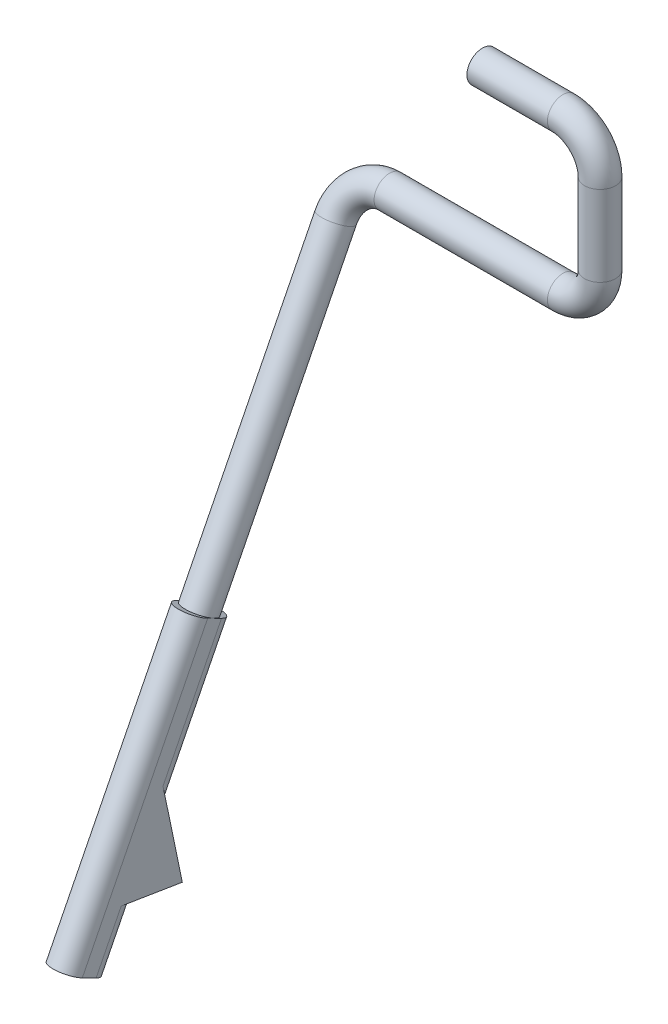
SolidWorks part; units mm, degrees
material "Alloy Steel"
ref_plane "Front Plane" through (0, 0, 0) normal (0, 0, 1) x (1, 0, 0)
ref_plane "Top Plane" through (0, 0, 0) normal (0, 1, 0) x (1, 0, 0)
ref_plane "Right Plane" through (0, 0, 0) normal (1, 0, 0) x (0, 0, -1)
sketch "Sketch2" plane through (0, 0, 0) normal (0, 0, 1) x (1, 0, 0)
  line L0 (0, 0) -> (-13, 0)
  line L1 (6, -6) -> (6, -25)
  arc A0 (0, 0) -> (6, -6) centre (0, -6) cw
  point P6 (6, 0)
  dimension "D3" = 6
  dimension "D1" = 19
  dimension "D2" = 25
sketch3d "3DSketch2"
  line L0 (0, -25, 0) -> (-28, -25, 0)
  line L1 (6, -25, 0) -> (-34, -25, 0) construction
  line L3 (-34, -30.3582, 2.7) -> (-34, -114.3029, 45)
  line L4 (-34, -25, 0) -> (-34, -25, 45) construction
  line L5 (0, 0, 0) -> (-13, 0, 0) construction
  line L6 (6, -6, 0) -> (6, -25, 0) construction
  line L7 (0, 0, 0) -> (-13, 0, 0)
  line L8 (6, -6, 0) -> (6, -19, 0)
  arc A0 (0, 0, 0) -> (6, -6, 0) centre (0, -6, 0) ccw construction
  arc A1 (0, 0, 0) -> (6, -6, 0) centre (0, -6, 0) ccw
  arc A2 (-28, -25, 0) -> (-34, -30.3582, 2.7) centre (-28, -30.3582, 2.7) ccw
  arc A3 (0, -25, 0) -> (6, -19, 0) centre (0, -19, 0) ccw
  point P10 (0, -6, -6)
  point P12 (0, -6, -6)
  point P15 (-34, -25, 0)
  point P17 (-28, -27.6582, 8.0582)
  point P20 (6, -25, 0)
  point P22 (0, -19, 6)
  dimension "D5" = 6
  dimension "D1" = 40
  dimension "D3" = 100
  dimension "D4" = 45
ref_plane "Plane1" through (-13, 0, 0) normal (1, 0, 0) x (0, 0, -1)
sketch "Sketch3" plane through (-13, 0, 0) normal (1, 0, 0) x (0, 0, -1)
  circle A0 centre (0, 0) radius 2.5
  dimension "D1" = 5
sweep "Sweep1" add profiles "Sketch3" path "3DSketch2"
sketch "Sketch4" plane through (0, -109.2404, 55.0466) normal (0, -0.893, 0.45) x (1, 0, 0)
  line L0 (-34, -10) -> (-34, -12.5) construction
  line L1 (-31.5, -10) -> (-31.5, -12.5)
  line L2 (-36.5, -10) -> (-36.5, -12.5)
  arc A0 (-31.5, -10) -> (-36.5, -10) centre (-34, -10) ccw
  arc A1 (-36.5, -12.5) -> (-31.5, -12.5) centre (-34, -12.5) ccw
  circle A3 centre (-34, -11.25) radius 2.5
  circle A4 centre (-34, -11.25) radius 2.5
  point P3 (-34, -11.25)
  circle M7 centre (-34, -11.25) radius 2.5
  dimension "D2" = 2.5
  dimension "D3" = 2.5
  dimension "D1" = 0
extrude "Boss-Extrude1" add sketch "Sketch4" against normal blind 45 contours L1 A0 L2 A4 M7 | L2 A1 L1 A4 M7 | L0 A4 M7 | L0 A4 M7
sketch "Sketch5" plane through (-31.5, 0, 0) normal (1, 0, 0) x (0, 0, -1)
  line L5 (-39.8337, -106.8281) -> (-29.9633, -108.4327)
  line L6 (-23.6337, -74.6791) -> (-43.8837, -114.8654) construction
  line L7 (-29.9633, -108.4327) -> (-33.0837, -93.4327)
  line L8 (-33.0837, -93.4327) -> (-39.8337, -106.8281)
  line L9 (-46.1163, -113.7404) -> (-43.8837, -114.8654) construction
  dimension "D1" = 9
  dimension "D2" = 10
  dimension "D3" = 15
  dimension "D4" = 15
extrude "Boss-Extrude2" add sketch "Sketch5" against normal up to surface (5 mm away) up to face at (-36.5, -90.1911, 32.85)
